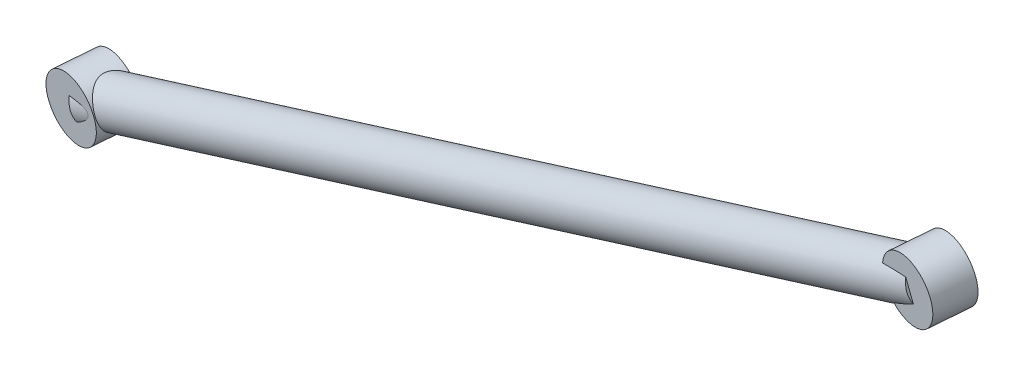
SolidWorks part; units mm, degrees
ref_plane "Plano frontal" through (0, 0, 0) normal (0, 0, 1) x (1, 0, 0)
ref_plane "Plano superior" through (0, 0, 0) normal (0, 1, 0) x (1, 0, 0)
ref_plane "Plano direito" through (0, 0, 0) normal (1, 0, 0) x (0, 0, -1)
sketch3d "SUSP_FL_tie_rod_eixo"
  line L0 (-270, -90.4, -82.3915) -> (-590.2935, -204.9905, -103.7504)
sweep "SUSP_FL_tie_rod" add path "SUSP_FL_tie_rod_eixo" circular profile diameter 16 parameters "D3"=16
sketch3d "SUSP_FL_tie_rod_rod_end_in_eixo"
  line L0 (-271.2111, -91.0009, -75.5233) -> (-268.7889, -89.7991, -89.2597)
sweep "SUSP_FL_tie_rod_rod_end_in" add path "SUSP_FL_tie_rod_rod_end_in_eixo" circular profile diameter 22 parameters "D3"=22
sketch3d "SUSP_FL_tie_rod_rod_end_out_eixo"
  line L0 (-591.5046, -205.5914, -96.8822) -> (-589.0825, -204.3896, -110.6186)
sweep "SUSP_FL_tie_rod_rod_end_out" add path "SUSP_FL_tie_rod_rod_end_out_eixo" circular profile diameter 22 parameters "D3"=22
sketch3d "REF_SKETCH"
  line L0 (-274, -92.8, -84.1915) -> (-266, -88, -80.5915)
  line L1 (-267.6, -93.4, -85.5915) -> (-272.4, -87.4, -79.1915)
  line L2 (-594.2935, -207.3905, -105.5504) -> (-586.2935, -202.5905, -101.9504)
  line L3 (-587.8935, -207.9905, -106.9504) -> (-592.6935, -201.9905, -100.5504)
ref_point "P_IN"
ref_point "P_OUT"
